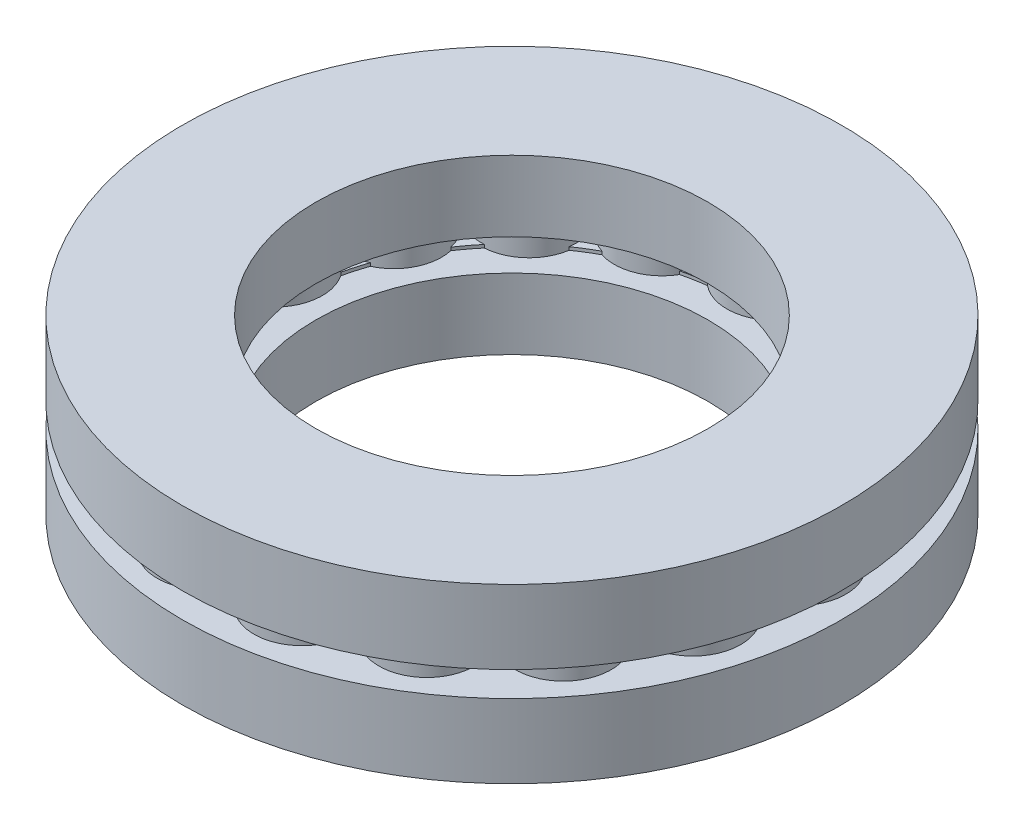
SolidWorks part; units mm, degrees
other "标注1"
sketch "草图7" plane through (21, 0, -21) normal (0.1502, -0.3112, -0.9384) x (-0.684, -0.718, 0.1286)
ref_plane "前视基准面" through (0, 0, 0) normal (0, 0, 1) x (1, 0, 0)
ref_plane "上视基准面" through (0, 0, 0) normal (0, 1, 0) x (1, 0, 0)
ref_plane "右视基准面" through (0, 0, 0) normal (1, 0, 0) x (0, 0, -1)
sketch "草图1" plane through (0, 0, 0) normal (0, 1, 0) x (1, 0, 0)
  circle A0 centre (0, 0) radius 21
  circle A1 centre (0, 0) radius 12.5
  dimension "D1" = 42
  dimension "D2" = 25
extrude "凸台-拉伸1" add sketch "草图1" along normal blind 4.5
sketch "草图2" plane through (0, 4.5, 0) normal (0, 1, 0) x (1, 0, 0)
  circle A0 centre (0, 16.75) radius 4.25
  circle A1 centre (0, 0) radius 12.5 construction
  circle A2 centre (0, 0) radius 21 construction
  circle A3 centre (0, 16.75) radius 3.05
  circle A4 centre (6.0508, 15.6189) radius 3.05
  circle A5 centre (11.2844, 12.3784) radius 3.05
  circle A6 centre (14.994, 7.4661) radius 3.05
  circle A7 centre (16.6785, 1.5455) radius 3.05
  circle A8 centre (16.1106, -4.5839) radius 3.05
  circle A9 centre (13.3668, -10.0941) radius 3.05
  circle A10 centre (8.8177, -14.2411) radius 3.05
  circle A11 centre (3.0778, -16.4648) radius 3.05
  circle A12 centre (-3.0778, -16.4648) radius 3.05
  circle A13 centre (-8.8177, -14.2411) radius 3.05
  circle A14 centre (-13.3668, -10.0941) radius 3.05
  circle A15 centre (-16.1106, -4.5839) radius 3.05
  circle A16 centre (-16.6785, 1.5455) radius 3.05
  circle A17 centre (-14.994, 7.4661) radius 3.05
  circle A18 centre (-11.2844, 12.3784) radius 3.05
  circle A19 centre (-6.0508, 15.6189) radius 3.05
  point P43 (0, 0)
  dimension "D1" = 1.2
  dimension "D2" = 17
extrude "凸台-拉伸3" add sketch "草图2" along normal blind 3.5 contours A3 | A4 | A5 | A6 | A7 | A8 | A9 | A10 | A11 | A12 | A13 | A14 | A15 | A16 | A17 | A18 | A19
ref_plane "基准面1" through (0, 6.5, 0) normal (0, 1, 0) x (1, 0, 0)
sketch "草图3" plane through (0, 6.5, 0) normal (0, 1, 0) x (1, 0, 0)
  circle A0 centre (0, 0) radius 12.5 construction
  circle A1 centre (0, 0) radius 21 construction
  circle A2 centre (0, 0) radius 12.5
  circle A3 centre (0, 0) radius 21
  circle A4 centre (0, 0) radius 14.5
  dimension "D1" = 29
extrude "凸台-拉伸4" add sketch "草图3" against normal blind 0.2 separate body contours A3 A4
sketch "草图5" plane through (0, 4.5, 0) normal (0, 1, 0) x (1, 0, 0)
  circle A0 centre (0, 0) radius 14.5 construction
  circle A1 centre (0, 0) radius 21
  circle A2 centre (0, 0) radius 21
  circle A3 centre (0, 0) radius 14.5
  dimension "D1" = 0
extrude "凸台-拉伸8" add sketch "草图5" along normal blind 0.2
sketch "草图6" plane through (0, 6.5, 0) normal (0, 1, 0) x (1, 0, 0)
  circle A0 centre (0, 0) radius 21 construction
  circle A1 centre (0, 0) radius 21
  circle A2 centre (0, 0) radius 12.5 construction
  circle A3 centre (0, 0) radius 12.5
extrude "凸台-拉伸9" add sketch "草图6" along normal blind 4.5
